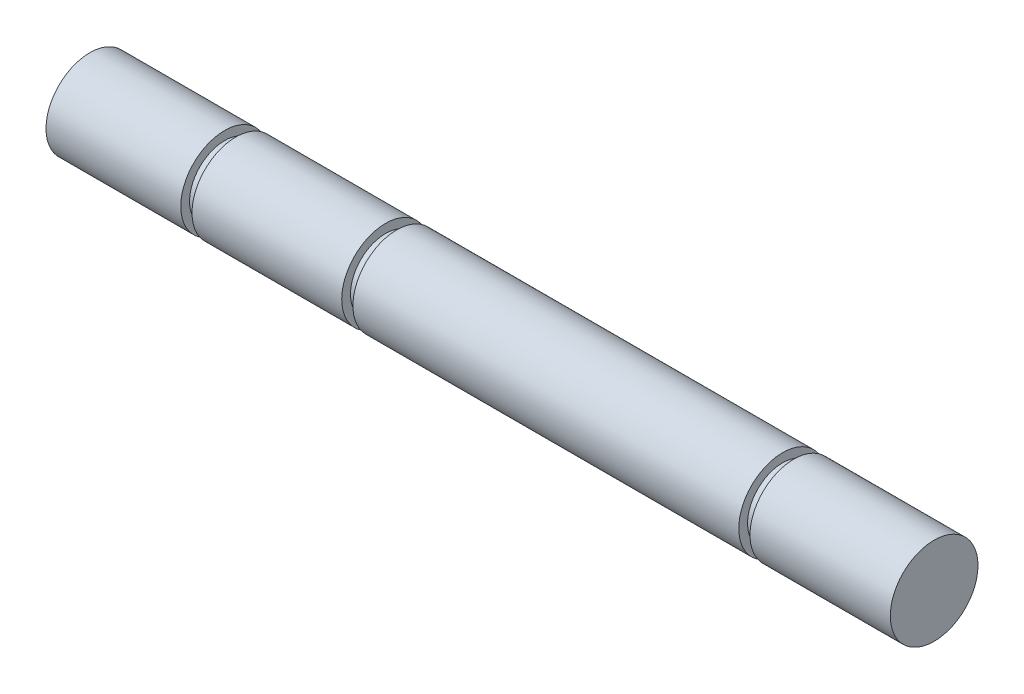
SolidWorks part; units mm, degrees
material "Plain Carbon Steel"
ref_plane "Front Plane" through (0, 0, 0) normal (0, 0, 1) x (1, 0, 0)
ref_plane "Top Plane" through (0, 0, 0) normal (0, 1, 0) x (1, 0, 0)
ref_plane "Right Plane" through (0, 0, 0) normal (1, 0, 0) x (0, 0, -1)
sketch "Sketch1" plane through (0, 0, 0) normal (1, 0, 0) x (0, 0, -1)
  circle A0 centre (0, 0) radius 2.5
  dimension "D1" = 5
extrude "Boss-Extrude1" add sketch "Sketch1" along normal blind 100
ref_plane "Plane1" through (92, 0, 0) normal (1, 0, 0) x (0, 0, -1)
sketch "Sketch2" plane through (92, 0, 0) normal (1, 0, 0) x (0, 0, -1)
  circle A0 centre (0, 0) radius 2
  circle A1 centre (0, 0) radius 2.5
  dimension "D1" = 4
  dimension "D2" = 5
extrude "Cut-Extrude1" cut sketch "Sketch2" against normal blind 0.64
ref_plane "Plane2" through (69.36, 0, 0) normal (1, 0, 0) x (0, 0, -1)
sketch "Sketch3" plane through (69.36, 0, 0) normal (1, 0, 0) x (0, 0, -1)
  circle A0 centre (0, 0) radius 2.5
  circle A1 centre (0, 0) radius 2
  dimension "D1" = 4
  dimension "D2" = 5
extrude "Cut-Extrude2" cut sketch "Sketch3" against normal blind 0.64
ref_plane "Plane3" through (51.86, 0, 0) normal (-1, 0, 0) x (0, 0, 1)
sketch "Sketch4" plane through (51.86, 0, 0) normal (-1, 0, 0) x (0, 0, 1)
  circle A0 centre (0, 0) radius 2.5
  dimension "D1" = 5
extrude "Cut-Extrude3" cut sketch "Sketch4" along normal up to surface (51.86 mm away) up to face at (0, 0, -2.5)
ref_plane "Plane4" through (60.185, 0, 0) normal (-1, 0, 0) x (0, 0, 1)
sketch "Sketch6" plane through (60.185, 0, 0) normal (-1, 0, 0) x (0, 0, 1)
  circle A0 centre (0, 0) radius 2
  circle A1 centre (0, 0) radius 2.5
  dimension "D1" = 5
  dimension "D2" = 4
extrude "Cut-Extrude4" cut sketch "Sketch6" along normal blind 0.64
